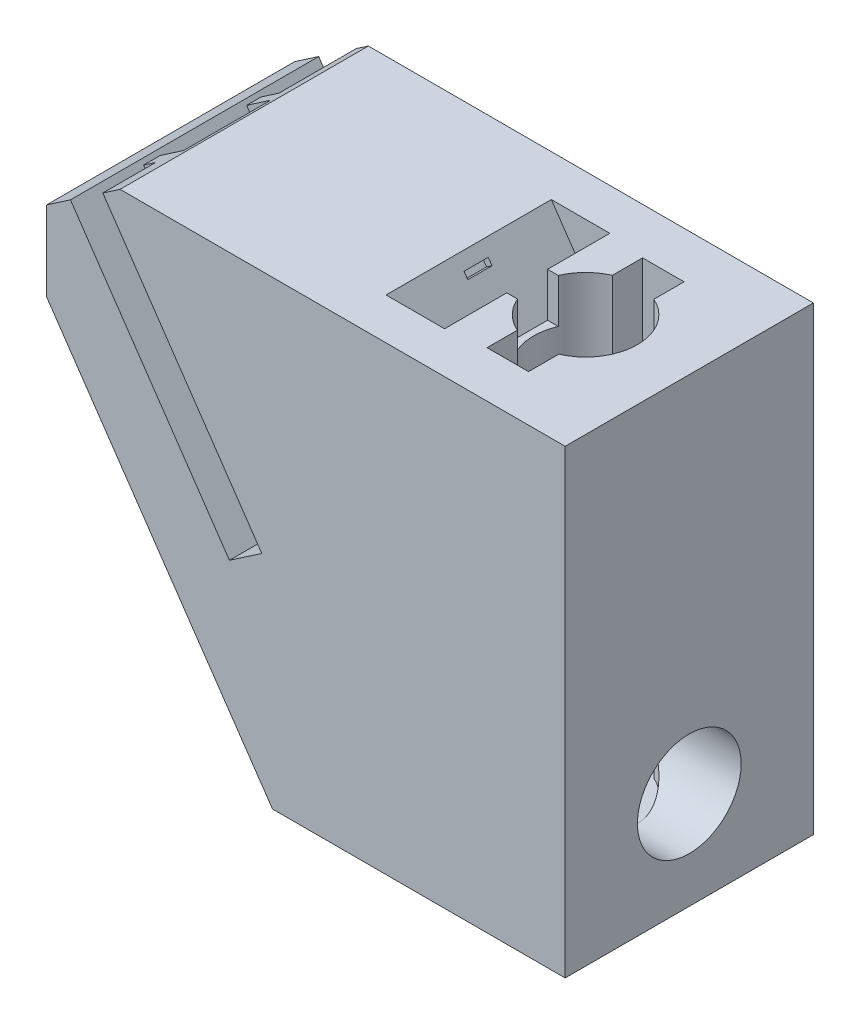
SolidWorks part; units mm, degrees
ref_plane "Front Plane" through (0, 0, 0) normal (0, 0, 1) x (1, 0, 0)
ref_plane "Top Plane" through (0, 0, 0) normal (0, 1, 0) x (1, 0, 0)
ref_plane "Right Plane" through (0, 0, 0) normal (1, 0, 0) x (0, 0, -1)
sketch "Sketch1" plane through (0, 0, 0) normal (0, 0, 1) x (1, 0, 0)
  line L6 (2.54, 23.749) -> (2.54, 14.224) construction
  line L7 (0, 0) -> (5.08, 0)
  line L8 (0, 0) -> (0, 14.224)
  line L9 (0, 14.224) -> (5.08, 14.224)
  line L14 (5.08, 0) -> (5.08, 14.224)
  line L19 (-4.6156, 24.384) -> (-4.0424, 23.5451)
  line L29 (-11.679, 6.821) -> (-21.27, 20.8572)
  line L31 (-22.86, -3.81) -> (8.89, -3.81)
  line L33 (-3.4692, 22.7063) -> (-1.0331, 19.1411)
  line L34 (-21.27, 20.8572) -> (-22.86, 19.7707)
  line L35 (-4.0424, 23.5451) -> (-3.4692, 22.7063)
  line L36 (-28.3165, 23.749) -> (25.4257, 23.749)
  line L37 (-28.3165, 23.749) -> (-28.3165, 38.989)
  line L38 (-28.3165, 38.989) -> (25.4257, 38.989)
  line L39 (25.4257, 23.749) -> (25.4257, 38.989)
  line L40 (2.54, 38.989) -> (2.54, 23.749) construction
  line L41 (2.54, 31.369) -> (-11.8891, 14.2184) construction
  line L42 (-21.27, 20.8572) -> (-17.9673, 23.1139)
  line L43 (-11.679, 6.821) -> (-8.3764, 9.0777)
  line L44 (-8.3764, 9.0777) -> (-9.5047, 10.729)
  line L45 (-1.0331, 19.1411) -> (0, 19.1411)
  line L46 (-17.9673, 23.1139) -> (-16.1085, 24.384)
  line L47 (-16.1085, 24.384) -> (-4.6156, 24.384)
  line L48 (0, 19.1411) -> (0, 14.224)
  line L49 (-4.329, 23.9646) -> (-17.443, 23.4721)
  line L50 (-4.329, 23.9646) -> (-3.7558, 23.1257)
  line L51 (-3.7558, 23.1257) -> (-8.3764, 9.0777)
  line L52 (-8.8063, 9.7068) -> (2.54, 42.6656) construction
  line L53 (2.54, 38.989) -> (2.54, 42.6656) construction
  line L54 (8.89, -3.81) -> (8.89, 24.384)
  line L55 (8.89, 24.384) -> (5.08, 24.384)
  line L56 (5.08, 14.224) -> (5.08, 24.384)
  line L57 (2.54, 23.749) -> (-4.0424, 23.5451) construction
  line L58 (2.54, 38.989) -> (-4.0424, 23.5451) construction
  line L59 (-4.0424, 23.5451) -> (-9.5047, 10.729) construction
  line L60 (-4.0424, 23.5451) -> (-17.9673, 23.1139) construction
  line L61 (-17.9673, 23.1139) -> (-9.5047, 10.729)
  line L62 (-8.8063, 9.7068) -> (-9.8549, 8.9903) construction
  line L63 (-9.8549, 8.9903) -> (-18.2379, 21.2588) construction
  line L64 (-18.2379, 21.2588) -> (-17.1893, 21.9753) construction
  line L69 (-17.1893, 21.9753) -> (2.54, 24.3311) construction
  line L70 (-22.86, 19.7707) -> (-22.86, -3.81)
  dimension "D1" = 5.08
  dimension "D2" = 14.224
  dimension "D3" = 0.635
  dimension "D4" = 10.16
  dimension "D5" = 4
  dimension "D6" = 15.24
  dimension "D7" = 17
  dimension "D8" = 31.75
  dimension "D9" = 1.59
  dimension "D10" = 1.016
  dimension "D11" = 6.35
  dimension "D12" = 3.81
  dimension "D13" = 3.81
  dimension "D14" = 0.635
  dimension "D15" = 0.508
  dimension "D16" = 0.508
  dimension "D17" = 0.762
  dimension "D18" = 14.859
  dimension "D19" = 1.27
  dimension "D20" = 15
extrude "Boss-Extrude1" add sketch "Sketch1" along normal blind 2.5 contours L34 L70 L31 L54 L36 L56 L14 L7 L8 L48 L45 L33 L35 L19 L46 L61 L44 L43 L29 | L47 L46 L36 L19 | L56 L36 L54 L55
sketch "Sketch2" plane through (0, 0, 2.5) normal (0, 0, 1) x (1, 0, 0)
  line L0 (-21.27, 20.8572) -> (-11.679, 6.821)
  line L1 (-21.27, 20.8572) -> (-18.0093, 23.0852)
  line L2 (-11.679, 6.821) -> (-8.4184, 9.049)
  line L3 (-18.0093, 23.0852) -> (-8.4184, 9.049)
  line L4 (-18.0093, 23.0852) -> (-16.1085, 24.384)
  line L5 (-16.1085, 24.384) -> (8.89, 24.384)
  line L6 (8.89, 24.384) -> (8.89, -3.81)
  line L7 (8.89, -3.81) -> (-22.86, -3.81)
  line L8 (-22.86, -3.81) -> (-22.86, 19.7707)
  line L9 (-22.86, 19.7707) -> (-21.27, 20.8572)
  line M1 (-21.27, 20.8572) -> (-22.86, 19.7707)
  line M2 (-22.86, 19.7707) -> (-22.86, -3.81)
  line M3 (-22.86, -3.81) -> (8.89, -3.81)
  line M4 (8.89, -3.81) -> (8.89, 24.384)
  line M5 (8.89, 24.384) -> (5.08, 24.384)
  line M6 (5.08, 24.384) -> (5.08, 0)
  line M7 (5.08, 0) -> (0, 0)
  line M8 (0, 0) -> (0, 19.1411)
  line M9 (0, 19.1411) -> (-1.0331, 19.1411)
  line M10 (-1.0331, 19.1411) -> (-3.7558, 23.1257)
  line M11 (-3.7558, 23.1257) -> (-8.3764, 9.0777)
  line M12 (-8.3764, 9.0777) -> (-11.679, 6.821)
  line M13 (-11.679, 6.821) -> (-21.27, 20.8572)
extrude "Boss-Extrude2" add sketch "Sketch2" along normal blind 6.35 contours M13 M1 M2 M3 M4 M5 M6 M7 M8 M9 M10 M11 M12 | L5 L4 L3 M12 M11 M10 M9 M8 M7 M6
sketch "Sketch3" plane through (0, 0, 0) normal (0, 0, -1) x (-1, 0, 0)
  line L0 (-8.89, 24.384) -> (-8.89, -3.81)
  line L1 (-8.89, -3.81) -> (22.86, -3.81)
  line L2 (22.86, -3.81) -> (22.86, 19.7707)
  line L3 (22.86, 19.7707) -> (21.27, 20.8572)
  line L4 (21.27, 20.8572) -> (11.679, 6.821)
  line L5 (11.679, 6.821) -> (8.3764, 9.0777)
  line L6 (8.3764, 9.0777) -> (18.0093, 23.0852)
  line L7 (18.0093, 23.0852) -> (16.1085, 24.384)
  line L8 (16.1085, 24.384) -> (-8.89, 24.384)
extrude "Boss-Extrude3" add sketch "Sketch3" along normal blind 6.35
sketch "Sketch4" plane through (0, 24.384, 0) normal (0, 1, 0) x (1, 0, 0)
  line L0 (2.54, 0) -> (2.54, -2.5) construction
  line L1 (-4.6156, 0) -> (5.08, 0) construction
  line L2 (5.08, -2.5) -> (-4.6156, -2.5) construction
  line L3 (-22.86, 0) -> (8.89, 0) construction
  line L4 (5.08, -2.5) -> (5.08, 0) construction
  circle A0 centre (2.54, -1.25) radius 3.175
  dimension "D2" = 6.35
  dimension "D1" = 2.54
extrude "Cut-Extrude1" cut sketch "Sketch4" against normal blind 25.4
sketch "Sketch5" plane through (0, -1.016, 0) normal (0, 1, 0) x (1, 0, 0)
  circle A0 centre (2.54, -1.25) radius 1.5875
  circle A1 centre (2.54, -1.25) radius 3.175
  circle A2 centre (2.54, -1.25) radius 3.175 construction
  dimension "D2" = 3.175
  dimension "D1" = 0
extrude "Cut-Extrude2" cut sketch "Sketch5" against normal blind 25.4
sketch "Sketch6" plane through (0, 0, 8.85) normal (0, 0, 1) x (1, 0, 0)
  line L0 (-22.86, 16.4309) -> (-9.0294, -3.81)
  line L1 (-22.86, 19.7707) -> (-22.86, -3.81) construction
  line L2 (-22.86, -3.81) -> (8.89, -3.81) construction
  line L3 (-11.679, 6.821) -> (-21.27, 20.8572) construction
  line L4 (-22.86, 16.4309) -> (-22.86, -3.81)
  line L5 (-22.86, -3.81) -> (-9.0294, -3.81)
  dimension "D1" = 3.81
extrude "Cut-Extrude3" cut sketch "Sketch6" against normal blind 25.4
sketch "Sketch7" plane through (8.89, 0, 0) normal (1, 0, 0) x (0, 0, -1)
  line L0 (1.925, -1.016) -> (-4.425, -1.016) construction
  line L1 (1.925, -1.016) -> (-4.425, -1.016)
  line L2 (-8.85, 2.159) -> (6.35, 2.159) construction
  line L3 (-8.85, -3.81) -> (-8.85, 24.384) construction
  line L4 (6.35, 24.384) -> (6.35, -3.81) construction
  circle A0 centre (-1.25, 2.159) radius 3.175
  dimension "D1" = 6.35
extrude "Cut-Extrude4" cut sketch "Sketch7" against normal up to next contours L2 A0 | A0 L2
sketch "Sketch8" plane through (0, 24.384, 0) normal (0, 1, 0) x (1, 0, 0)
  line L1 (1.27, -6.0125) -> (3.81, -6.0125)
  line L2 (1.27, -6.0125) -> (1.27, 3.5125)
  line L3 (1.27, 3.5125) -> (3.81, 3.5125)
  line L4 (3.81, -6.0125) -> (3.81, 3.5125)
  line L5 (1.27, -6.0125) -> (3.81, 3.5125) construction
  line L6 (1.27, 3.5125) -> (3.81, -6.0125) construction
  point P0 (2.54, -1.25)
  dimension "D1" = 9.525
  dimension "D2" = 2.54
extrude "Cut-Extrude5" cut sketch "Sketch8" against normal up to surface (25.4 mm away) up to face at (2.54, -1.016, 2.8375)
sketch "Sketch9" plane through (-6.8946, 10.0902, 0) normal (-0.5642, 0.8257, 0) x (0.8257, 0.5642, 0)
  line L1 (-1.8455, -4.6028) -> (-3.5726, -4.6028)
  line L2 (-3.5726, -4.6028) -> (-3.5726, -5.6188)
  line L3 (-3.5726, -5.6188) -> (-2.6836, -5.6188)
  line L4 (-2.6836, -5.6188) -> (-2.6836, -8.85)
  line L5 (-1.8455, -8.85) -> (-5.7946, -8.85) construction
  line L6 (-2.6836, -8.85) -> (-1.8455, -8.85)
  line L9 (-1.7946, 6.35) -> (-1.7946, 0) construction
  line L10 (-3.6235, 0.7312) -> (-3.6235, 1.6202)
  line L11 (-1.7946, 0.7312) -> (-3.6235, 0.7312)
  line L12 (-2.7091, 0.7312) -> (-2.7091, -4.6028) construction
  line L13 (-5.7946, 6.35) -> (-5.0834, 6.35)
  line L14 (-5.7946, 6.35) -> (-5.7946, -8.85)
  line L15 (-5.7946, -8.85) -> (-5.0834, -8.85)
  line L16 (-5.0834, 6.35) -> (-5.0834, -8.85)
  line L17 (-0.6688, -2.5) -> (-0.6688, 0) construction
  line L18 (-1.8455, -8.85) -> (-1.8455, -2.5) construction
  line L19 (-3.6235, 1.6202) -> (-2.3026, 1.6202)
  line L20 (-2.3026, 1.6202) -> (-2.3026, 6.35)
  line L21 (-5.7946, 6.35) -> (-1.7946, 6.35) construction
  line L23 (-1.7946, -2.5) -> (-1.7946, 0) construction
  line L24 (-1.7946, 0.7312) -> (-1.7946, 6.35)
  line L27 (-1.8455, 6.35) -> (0.4567, 6.35) construction
  line L28 (-2.3026, 6.35) -> (-1.7946, 6.35)
  point P28 (-0.6688, -1.25)
  line M15 (-1.7946, 0) -> (-1.7946, 6.35)
  line M16 (-1.7946, 6.35) -> (-5.7946, 6.35)
  line M17 (-5.7946, 6.35) -> (-5.7946, -8.85)
  line M18 (-5.7946, -8.85) -> (-1.8455, -8.85)
  line M19 (-1.8455, -8.85) -> (-1.8455, -2.5)
  dimension "D1" = 0.7112
  dimension "D2" = 5.334
  dimension "D3" = 1.9812
  dimension "D4" = 0.508
  dimension "D5" = 0.889
  dimension "D6" = 0.889
  dimension "D7" = 1.016
  dimension "D8" = 1.778
extrude "Boss-Extrude4" add sketch "Sketch9" along normal up to surface (17 mm away) contours L16 M16 M17 M18 | L20 L19 L10 L11 M15 M16 | L3 L4 L1 L2 M18 M19 up to face at (-17.2912, 23.5758, 1.25)
sketch "Sketch10" plane through (-6.8946, 10.0902, 0) normal (-0.5642, 0.8257, 0) x (0.8257, 0.5642, 0)
  line L15 (-5.0834, -8.85) -> (-2.6836, -8.85)
  line L16 (-2.6836, -8.85) -> (-2.6836, -5.6188)
  line L17 (-2.6836, -5.6188) -> (-3.5726, -5.6188)
  line L18 (-3.5726, -5.6188) -> (-3.5726, -4.6028)
  line L19 (-3.5726, -4.6028) -> (-1.8455, -4.6028)
  line L20 (-1.8455, -4.6028) -> (-1.8455, -2.5)
  line L21 (-1.8455, -2.5) -> (-1.7946, -2.5)
  line L22 (-1.7946, -2.5) -> (-1.7946, 0)
  line L23 (-1.7946, 0) -> (-1.7946, 0.7312)
  line L24 (-1.7946, 0.7312) -> (-3.6235, 0.7312)
  line L25 (-3.6235, 0.7312) -> (-3.6235, 1.6202)
  line L26 (-3.6235, 1.6202) -> (-2.3026, 1.6202)
  line L27 (-2.3026, 1.6202) -> (-2.3026, 6.35)
  line L28 (-2.3026, 6.35) -> (-5.0834, 6.35)
  line L29 (-5.0834, 6.35) -> (-5.0834, -8.85)
  line L30 (-5.0834, -8.85) -> (-2.6836, -8.85)
  line L31 (-2.6836, -8.85) -> (-2.6836, -5.6188)
  line L32 (-2.6836, -5.6188) -> (-3.5726, -5.6188)
  line L33 (-3.5726, -5.6188) -> (-3.5726, -4.6028)
  line L34 (-3.5726, -4.6028) -> (-1.8455, -4.6028)
  line L35 (-1.8455, -4.6028) -> (-1.8455, -2.5)
  line L36 (-1.8455, -2.5) -> (-1.7946, -2.5)
  line L37 (-1.7946, -2.5) -> (-1.7946, 0)
  line L38 (-1.7946, 0) -> (-1.7946, 0.7312)
  line L39 (-1.7946, 0.7312) -> (-3.6235, 0.7312)
  line L40 (-3.6235, 0.7312) -> (-3.6235, 1.6202)
  line L41 (-3.6235, 1.6202) -> (-2.3026, 1.6202)
  line L42 (-2.3026, 1.6202) -> (-2.3026, 6.35)
  line L43 (-2.3026, 6.35) -> (-5.0834, 6.35)
  line L44 (-5.0834, 6.35) -> (-5.0834, -8.85)
  dimension "D1" = 0
extrude "Boss-Extrude5" add sketch "Sketch10" along normal blind 1.016
sketch "Sketch11" plane through (-16.4856, 24.1263, 0) normal (-0.5642, 0.8257, 0) x (0.8257, 0.5642, 0)
  line L0 (-7.7204, -8.85) -> (-5.0834, -8.85) construction
  line L1 (-5.0834, -8.85) -> (-5.0834, 6.35) construction
  line L2 (-5.0834, 6.35) -> (-7.7204, 6.35) construction
  line L3 (-7.7204, 6.35) -> (-7.7204, -8.85) construction
  line L4 (-3.6235, 0.7312) -> (-1.8455, 0.7312) construction
  line L5 (-1.8455, 0.7312) -> (-1.8455, 0) construction
  line L6 (-1.8455, 0) -> (-0.6688, 0) construction
  line L7 (-0.6688, 0) -> (-0.6688, -2.5) construction
  line L8 (-0.6688, -2.5) -> (-1.8455, -2.5) construction
  line L9 (-1.8455, -2.5) -> (-1.8455, -4.6028) construction
  line L10 (-1.8455, -4.6028) -> (-3.5726, -4.6028) construction
  line L11 (-3.5726, -4.6028) -> (-3.5726, -5.6188) construction
  line L12 (-3.5726, -5.6188) -> (-2.6836, -5.6188) construction
  line L13 (-2.6836, -5.6188) -> (-2.6836, -8.85) construction
  line L14 (-2.6836, -8.85) -> (0.4567, -8.85) construction
  line L15 (0.4567, -8.85) -> (0.4567, 6.35) construction
  line L16 (0.4567, 6.35) -> (-2.3026, 6.35) construction
  line L17 (-2.3026, 6.35) -> (-2.3026, 1.6202) construction
  line L18 (-2.3026, 1.6202) -> (-3.6235, 1.6202) construction
  line L19 (-3.6235, 1.6202) -> (-3.6235, 0.7312) construction
  line L20 (-7.7204, -8.85) -> (-5.0834, -8.85)
  line L21 (-5.0834, -8.85) -> (-5.0834, 6.35)
  line L22 (-5.0834, 6.35) -> (-7.7204, 6.35)
  line L23 (-7.7204, 6.35) -> (-7.7204, -8.85)
  line L24 (-3.6235, 0.7312) -> (-1.8455, 0.7312)
  line L25 (-1.8455, 0.7312) -> (-1.8455, 0)
  line L26 (-1.8455, 0) -> (-0.6688, 0)
  line L27 (-0.6688, 0) -> (-0.6688, -2.5)
  line L28 (-0.6688, -2.5) -> (-1.8455, -2.5)
  line L29 (-1.8455, -2.5) -> (-1.8455, -4.6028)
  line L30 (-1.8455, -4.6028) -> (-3.5726, -4.6028)
  line L31 (-3.5726, -4.6028) -> (-3.5726, -5.6188)
  line L32 (-3.5726, -5.6188) -> (-2.6836, -5.6188)
  line L33 (-2.6836, -5.6188) -> (-2.6836, -8.85)
  line L34 (-2.6836, -8.85) -> (0.4567, -8.85)
  line L35 (0.4567, -8.85) -> (0.4567, 6.35)
  line L36 (0.4567, 6.35) -> (-2.3026, 6.35)
  line L37 (-2.3026, 6.35) -> (-2.3026, 1.6202)
  line L38 (-2.3026, 1.6202) -> (-3.6235, 1.6202)
  line L39 (-3.6235, 1.6202) -> (-3.6235, 0.7312)
  line L41 (-1.8455, 0) -> (-0.6688, 0)
  line L42 (-1.8455, 0) -> (-1.8455, -2.5)
  line L43 (-1.8455, -2.5) -> (-0.6688, -2.5)
  line L44 (-0.6688, 0) -> (-0.6688, -2.5)
  line M25 (-3.6235, 0.7312) -> (-1.8455, 0.7312)
  line M26 (-1.8455, 0.7312) -> (-1.8455, 0)
  line M27 (-1.8455, 0) -> (-0.6688, 0)
  line M28 (-0.6688, 0) -> (-0.6688, -2.5)
  line M29 (-0.6688, -2.5) -> (-1.8455, -2.5)
  line M30 (-1.8455, -2.5) -> (-1.8455, -4.6028)
  line M31 (-1.8455, -4.6028) -> (-3.5726, -4.6028)
  line M32 (-3.5726, -4.6028) -> (-3.5726, -5.6188)
  line M33 (-3.5726, -5.6188) -> (-2.6836, -5.6188)
  line M34 (-2.6836, -5.6188) -> (-2.6836, -8.85)
  line M35 (-2.6836, -8.85) -> (0.4567, -8.85)
  line M36 (0.4567, -8.85) -> (0.4567, 6.35)
  line M37 (0.4567, 6.35) -> (-2.3026, 6.35)
  line M38 (-2.3026, 6.35) -> (-2.3026, 1.6202)
  line M39 (-2.3026, 1.6202) -> (-3.6235, 1.6202)
  line M40 (-3.6235, 1.6202) -> (-3.6235, 0.7312)
extrude "Boss-Extrude6" add sketch "Sketch11" along normal blind 1.27 contours L42 M27 M29 M28 | M40 M25 M26 M27 M28 M29 M30 M31 M32 M33 M34 M35 M36 M37 M38 M39 | L22 L23 L20 L21
sketch "Sketch12" plane through (0, 0, 8.85) normal (0, 0, 1) x (1, 0, 0)
  line L0 (-16.1085, 24.384) -> (-18.3596, 24.384)
  line L1 (-19.4178, 23.6609) -> (-16.825, 25.4326) construction
  line L2 (-18.3596, 24.384) -> (-16.825, 25.4326)
  line L3 (-16.825, 25.4326) -> (-16.1085, 24.384)
  line L4 (-22.86, 19.7707) -> (-22.86, 21.3089)
  line L5 (-23.5765, 20.8193) -> (-21.3993, 22.307) construction
  line L6 (-22.86, 21.3089) -> (-23.5765, 20.8193)
  line L7 (-23.5765, 20.8193) -> (-22.86, 19.7707)
extrude "Cut-Extrude6" cut sketch "Sketch12" against normal through all
sketch "Sketch13" plane through (0, 19.1411, 0) normal (0, 1, 0) x (1, 0, 0)
  line L3 (-0.3786, 0) -> (-1.0331, 0)
  line L4 (-1.0331, 0) -> (-1.0331, -2.5)
  line L5 (-1.0331, -2.5) -> (-0.3786, -2.5)
  line L6 (-0.3786, 0) -> (-1.0331, 0)
  line L7 (-1.0331, 0) -> (-1.0331, -2.5)
  line L8 (-1.0331, -2.5) -> (-0.3786, -2.5)
  arc A1 (-0.3786, 0) -> (-0.3786, -2.5) centre (2.54, -1.25) ccw
  arc A2 (-0.3786, 0) -> (-0.3786, -2.5) centre (2.54, -1.25) ccw
  dimension "D1" = 0
extrude "Boss-Extrude7" add sketch "Sketch13" along normal blind 2.54
sketch "Sketch14" plane through (8.2119, 5.6112, 0) normal (0.8257, 0.5642, 0) x (0, 0, -1)
  line L0 (0, 22.2288) -> (0, 22.7368) construction
  line L1 (0, 22.7368) -> (-2.5, 22.7368) construction
  line L2 (-2.5, 22.7368) -> (-2.5, 22.2288) construction
  line L3 (-2.5, 22.2288) -> (0, 22.2288) construction
  line L4 (0, 16.3868) -> (0, 21.2128) construction
  line L5 (0, 21.2128) -> (-2.5, 21.2128) construction
  line L6 (-2.5, 21.2128) -> (-2.5, 16.3868) construction
  line L7 (-2.5, 16.3868) -> (0, 16.3868) construction
  line L8 (0, 22.2288) -> (0, 22.7368)
  line L9 (0, 22.7368) -> (-2.5, 22.7368)
  line L10 (-2.5, 22.7368) -> (-2.5, 22.2288)
  line L11 (-2.5, 22.2288) -> (0, 22.2288)
  line L12 (0, 16.3868) -> (0, 21.2128)
  line L13 (0, 21.2128) -> (-2.5, 21.2128)
  line L14 (-2.5, 21.2128) -> (-2.5, 16.3868)
  line L15 (-2.5, 16.3868) -> (0, 16.3868)
  dimension "D1" = 2.5
sketch "Sketch15" plane through (0, 0, 0) normal (0, 0, 1) x (1, 0, 0)
  line L0 (-4.329, 23.9646) -> (-3.7558, 23.1257)
  line L1 (-4.329, 23.9646) -> (-4.6156, 24.384) construction
  line L2 (-3.7558, 23.1257) -> (-1.0331, 19.1411) construction
  line L3 (-4.2633, 23.1481) -> (-3.9277, 23.3774)
  line L4 (-4.4925, 23.4836) -> (-4.8089, 23.9465)
  line L5 (-4.8089, 23.9465) -> (-4.329, 23.9646)
  line L6 (-4.4925, 23.4836) -> (-4.157, 23.7129)
  line L7 (-4.2633, 23.1481) -> (-3.9157, 22.6394)
  line L8 (-3.9157, 22.6394) -> (-3.7558, 23.1257)
  line L9 (-4.0424, 23.5451) -> (-3.9209, 23.3673) construction
  line L10 (-4.0424, 23.5451) -> (-4.1638, 23.7229) construction
  line L11 (-1.0331, 19.1411) -> (-3.7558, 23.1257) construction
  line L25 (-1.0331, 19.1411) -> (-1.0331, 21.6811)
  line L26 (-1.0331, 21.6811) -> (-0.3786, 21.6811)
  line L27 (-0.3786, 21.6811) -> (-0.3786, 24.384)
  line L28 (-0.3786, 24.384) -> (-4.6156, 24.384)
  line L29 (-4.6156, 24.384) -> (-4.329, 23.9646)
  line L30 (-4.329, 23.9646) -> (-10.0694, 23.749)
  line L31 (-10.0694, 23.749) -> (-17.0378, 23.749)
  line L32 (-17.0378, 23.749) -> (-18.0093, 23.0852)
  line L33 (-18.0093, 23.0852) -> (-8.9521, 9.9148)
  line L34 (-8.9521, 9.9148) -> (-8.9496, 9.9166)
  line L35 (-8.9496, 9.9166) -> (-8.3764, 9.0777)
  line L36 (-8.3764, 9.0777) -> (-3.7558, 23.1257)
  line L37 (-3.7558, 23.1257) -> (-1.0331, 19.1411)
  line L38 (-1.0331, 19.1411) -> (-1.0331, 21.6811)
  line L39 (-1.0331, 21.6811) -> (-0.3786, 21.6811)
  line L40 (-0.3786, 21.6811) -> (-0.3786, 24.384)
  line L41 (-0.3786, 24.384) -> (-4.6156, 24.384)
  line L42 (-4.6156, 24.384) -> (-4.329, 23.9646)
  line L43 (-4.329, 23.9646) -> (-10.0694, 23.749)
  line L44 (-10.0694, 23.749) -> (-17.0378, 23.749)
  line L45 (-17.0378, 23.749) -> (-18.0093, 23.0852)
  line L46 (-18.0093, 23.0852) -> (-8.9521, 9.9148)
  line L47 (-8.9521, 9.9148) -> (-8.9496, 9.9166)
  line L48 (-8.9496, 9.9166) -> (-8.3764, 9.0777)
  line L49 (-8.3764, 9.0777) -> (-3.7558, 23.1257)
  line L50 (-3.7558, 23.1257) -> (-1.0331, 19.1411)
  line M26 (-4.329, 23.9646) -> (-10.0694, 23.749)
  line M32 (-8.3764, 9.0777) -> (-3.7558, 23.1257)
  dimension "D1" = 0.4064
  dimension "D2" = 0.4064
  dimension "D3" = 0
  dimension "D4" = 0.2032
extrude "Boss-Extrude8" add sketch "Sketch15" along normal blind 2.54 contours L4 L6 L0 M26 | L3 L7 L0 M32
sketch "Sketch16" plane through (0, 0, 0) normal (0, 0, 1) x (1, 0, 0)
  line L0 (-4.157, 23.7129) -> (-3.9277, 23.3774)
  line L1 (-4.2633, 23.1481) -> (-3.9277, 23.3774)
  line L2 (-4.2633, 23.1481) -> (-4.4925, 23.4836)
  line L3 (-4.4925, 23.4836) -> (-4.157, 23.7129)
  line L17 (-3.9157, 22.6394) -> (-4.2633, 23.1481)
  line L18 (-4.2633, 23.1481) -> (-3.9277, 23.3774)
  line L19 (-3.9277, 23.3774) -> (-1.0331, 19.1411)
  line L20 (-1.0331, 19.1411) -> (-1.0331, 21.6811)
  line L21 (-1.0331, 21.6811) -> (-0.3786, 21.6811)
  line L22 (-0.3786, 21.6811) -> (-0.3786, 24.384)
  line L23 (-0.3786, 24.384) -> (-4.6156, 24.384)
  line L24 (-4.6156, 24.384) -> (-4.157, 23.7129)
  line L25 (-4.157, 23.7129) -> (-4.4925, 23.4836)
  line L26 (-4.4925, 23.4836) -> (-4.8089, 23.9465)
  line L27 (-4.8089, 23.9465) -> (-10.0694, 23.749)
  line L28 (-10.0694, 23.749) -> (-17.0378, 23.749)
  line L29 (-17.0378, 23.749) -> (-18.0093, 23.0852)
  line L30 (-18.0093, 23.0852) -> (-8.9521, 9.9148)
  line L31 (-8.9521, 9.9148) -> (-8.9496, 9.9166)
  line L32 (-8.9496, 9.9166) -> (-8.3764, 9.0777)
  line L33 (-8.3764, 9.0777) -> (-3.9157, 22.6394)
  line L34 (-3.9157, 22.6394) -> (-4.2633, 23.1481)
  line L35 (-4.2633, 23.1481) -> (-3.9277, 23.3774)
  line L36 (-3.9277, 23.3774) -> (-1.0331, 19.1411)
  line L37 (-1.0331, 19.1411) -> (-1.0331, 21.6811)
  line L38 (-1.0331, 21.6811) -> (-0.3786, 21.6811)
  line L39 (-0.3786, 21.6811) -> (-0.3786, 24.384)
  line L40 (-0.3786, 24.384) -> (-4.6156, 24.384)
  line L41 (-4.6156, 24.384) -> (-4.157, 23.7129)
  line L42 (-4.157, 23.7129) -> (-4.4925, 23.4836)
  line L43 (-4.4925, 23.4836) -> (-4.8089, 23.9465)
  line L44 (-4.8089, 23.9465) -> (-10.0694, 23.749)
  line L45 (-10.0694, 23.749) -> (-17.0378, 23.749)
  line L46 (-17.0378, 23.749) -> (-18.0093, 23.0852)
  line L47 (-18.0093, 23.0852) -> (-8.9521, 9.9148)
  line L48 (-8.9521, 9.9148) -> (-8.9496, 9.9166)
  line L49 (-8.9496, 9.9166) -> (-8.3764, 9.0777)
  line L50 (-8.3764, 9.0777) -> (-3.9157, 22.6394)
  line M19 (-4.2633, 23.1481) -> (-3.9277, 23.3774)
  line M26 (-4.157, 23.7129) -> (-4.4925, 23.4836)
  dimension "D1" = 0
extrude "Boss-Extrude9" add sketch "Sketch16" along normal blind 0.508 contours L2 L0 M19 M26
sketch "Sketch17" plane through (0, 0, 2.5) normal (0, 0, -1) x (-1, 0, 0)
  line L0 (4.157, 23.7129) -> (3.9277, 23.3774)
  line L1 (3.9277, 23.3774) -> (4.2633, 23.1481)
  line L2 (4.2633, 23.1481) -> (4.4925, 23.4836)
  line L3 (4.4925, 23.4836) -> (4.157, 23.7129)
  line L17 (4.2633, 23.1481) -> (3.9157, 22.6394)
  line L18 (3.9157, 22.6394) -> (8.3764, 9.0777)
  line L19 (8.3764, 9.0777) -> (8.9496, 9.9166)
  line L20 (8.9496, 9.9166) -> (8.9916, 9.8879)
  line L21 (8.9916, 9.8879) -> (18.0093, 23.0852)
  line L22 (18.0093, 23.0852) -> (17.0378, 23.749)
  line L23 (17.0378, 23.749) -> (10.0694, 23.749)
  line L24 (10.0694, 23.749) -> (4.8089, 23.9465)
  line L25 (4.8089, 23.9465) -> (4.4925, 23.4836)
  line L26 (4.4925, 23.4836) -> (4.157, 23.7129)
  line L27 (4.157, 23.7129) -> (4.6156, 24.384)
  line L28 (4.6156, 24.384) -> (0.3786, 24.384)
  line L29 (0.3786, 24.384) -> (0.3786, 21.6811)
  line L30 (0.3786, 21.6811) -> (1.0331, 21.6811)
  line L31 (1.0331, 21.6811) -> (1.0331, 19.1411)
  line L32 (1.0331, 19.1411) -> (3.9277, 23.3774)
  line L33 (3.9277, 23.3774) -> (4.2633, 23.1481)
  line L34 (4.2633, 23.1481) -> (3.9157, 22.6394)
  line L35 (3.9157, 22.6394) -> (8.3764, 9.0777)
  line L36 (8.3764, 9.0777) -> (8.9496, 9.9166)
  line L37 (8.9496, 9.9166) -> (8.9916, 9.8879)
  line L38 (8.9916, 9.8879) -> (18.0093, 23.0852)
  line L39 (18.0093, 23.0852) -> (17.0378, 23.749)
  line L40 (17.0378, 23.749) -> (10.0694, 23.749)
  line L41 (10.0694, 23.749) -> (4.8089, 23.9465)
  line L42 (4.8089, 23.9465) -> (4.4925, 23.4836)
  line L43 (4.4925, 23.4836) -> (4.157, 23.7129)
  line L44 (4.157, 23.7129) -> (4.6156, 24.384)
  line L45 (4.6156, 24.384) -> (0.3786, 24.384)
  line L46 (0.3786, 24.384) -> (0.3786, 21.6811)
  line L47 (0.3786, 21.6811) -> (1.0331, 21.6811)
  line L48 (1.0331, 21.6811) -> (1.0331, 19.1411)
  line L49 (1.0331, 19.1411) -> (3.9277, 23.3774)
  line L50 (3.9277, 23.3774) -> (4.2633, 23.1481)
  line M27 (4.4925, 23.4836) -> (4.157, 23.7129)
  line M34 (3.9277, 23.3774) -> (4.2633, 23.1481)
  dimension "D1" = 0
extrude "Boss-Extrude10" add sketch "Sketch17" along normal blind 0.508 contours L2 L0 M34 M27
sketch "Sketch18" plane through (0, 0, 2.5) normal (0, 0, -1) x (-1, 0, 0)
  line L0 (1.0331, 21.6811) -> (1.0331, 24.384)
  line L5 (1.0331, 19.1411) -> (4.6156, 24.384)
  line L6 (4.6156, 24.384) -> (0.3786, 24.384)
  line L7 (0.3786, 24.384) -> (0.3786, 21.6811)
  line L8 (0.3786, 21.6811) -> (1.0331, 21.6811)
  line L9 (1.0331, 21.6811) -> (1.0331, 19.1411)
  line L10 (1.0331, 19.1411) -> (4.6156, 24.384)
  line L11 (4.6156, 24.384) -> (0.3786, 24.384)
  line L12 (0.3786, 24.384) -> (0.3786, 21.6811)
  line L13 (0.3786, 21.6811) -> (1.0331, 21.6811)
  line L14 (1.0331, 21.6811) -> (1.0331, 19.1411)
  line M6 (1.0331, 19.1411) -> (4.6156, 24.384)
  line M7 (4.6156, 24.384) -> (0.3786, 24.384)
  line M10 (1.0331, 21.6811) -> (1.0331, 19.1411)
  dimension "D1" = 0
extrude "Cut-Extrude7" cut sketch "Sketch18" against normal blind 3.81 contours L0 M10 M6 M7
sketch "Sketch19" plane through (0, 0, 0) normal (0, 0, 1) x (1, 0, 0)
  line L0 (-1.0331, 21.6811) -> (-1.0331, 24.384)
  line L5 (-0.3786, 24.384) -> (-4.6156, 24.384)
  line L6 (-4.6156, 24.384) -> (-1.0331, 19.1411)
  line L7 (-1.0331, 19.1411) -> (-1.0331, 21.6811)
  line L8 (-1.0331, 21.6811) -> (-0.3786, 21.6811)
  line L9 (-0.3786, 21.6811) -> (-0.3786, 24.384)
  line L10 (-0.3786, 24.384) -> (-4.6156, 24.384)
  line L11 (-4.6156, 24.384) -> (-1.0331, 19.1411)
  line L12 (-1.0331, 19.1411) -> (-1.0331, 21.6811)
  line L13 (-1.0331, 21.6811) -> (-0.3786, 21.6811)
  line L14 (-0.3786, 21.6811) -> (-0.3786, 24.384)
  line M6 (-0.3786, 24.384) -> (-4.6156, 24.384)
  line M7 (-4.6156, 24.384) -> (-1.0331, 19.1411)
  line M8 (-1.0331, 19.1411) -> (-1.0331, 21.6811)
  dimension "D1" = 0
extrude "Cut-Extrude8" cut sketch "Sketch19" against normal blind 3.81 contours L0 M8 M6 M7
sketch "Sketch20" plane through (0, 0, 0) normal (0, 0, 1) x (1, 0, 0)
  line L0 (-4.4925, 23.4836) -> (-10.0694, 23.749)
  line L8 (-8.3764, 9.0777) -> (-3.9157, 22.6394)
  line L9 (-3.9157, 22.6394) -> (-4.8089, 23.9465)
  line L10 (-4.8089, 23.9465) -> (-10.0694, 23.749)
  line L11 (-10.0694, 23.749) -> (-17.0378, 23.749)
  line L12 (-17.0378, 23.749) -> (-18.0093, 23.0852)
  line L13 (-18.0093, 23.0852) -> (-8.9521, 9.9148)
  line L14 (-8.9521, 9.9148) -> (-8.9496, 9.9166)
  line L15 (-8.9496, 9.9166) -> (-8.3764, 9.0777)
  line L16 (-8.3764, 9.0777) -> (-3.9157, 22.6394)
  line L17 (-3.9157, 22.6394) -> (-4.8089, 23.9465)
  line L18 (-4.8089, 23.9465) -> (-10.0694, 23.749)
  line L19 (-10.0694, 23.749) -> (-17.0378, 23.749)
  line L20 (-17.0378, 23.749) -> (-18.0093, 23.0852)
  line L21 (-18.0093, 23.0852) -> (-8.9521, 9.9148)
  line L22 (-8.9521, 9.9148) -> (-8.9496, 9.9166)
  line L23 (-8.9496, 9.9166) -> (-8.3764, 9.0777)
  point P6 (-10.0299, 23.749)
  line M10 (-3.9157, 22.6394) -> (-4.8089, 23.9465)
  line M11 (-4.8089, 23.9465) -> (-10.0694, 23.749)
  dimension "D1" = 0
extrude "Boss-Extrude11" add sketch "Sketch20" along normal blind 3.81 contours L0 M10 M11
